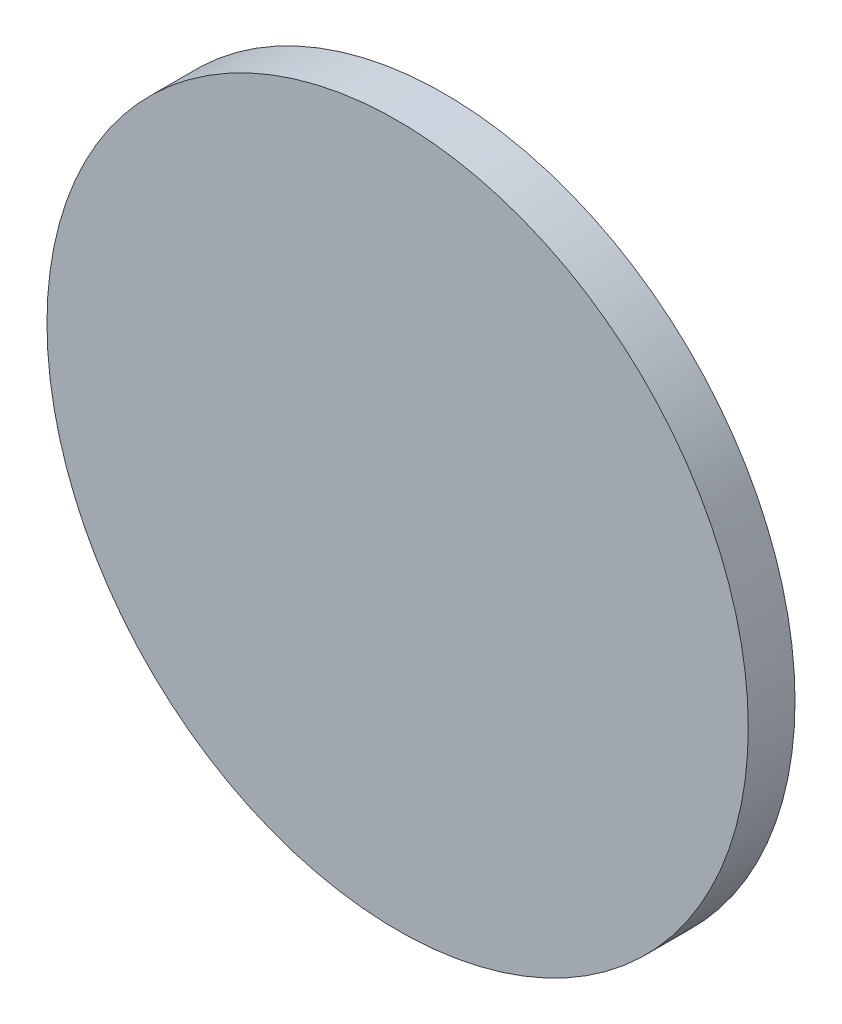
SolidWorks part; units mm, degrees
ref_plane "Front Plane" through (0, 0, 0) normal (0, 0, 1) x (1, 0, 0)
ref_plane "Top Plane" through (0, 0, 0) normal (0, 1, 0) x (1, 0, 0)
ref_plane "Right Plane" through (0, 0, 0) normal (1, 0, 0) x (0, 0, -1)
sketch "Sketch1" plane through (0, 0, 0) normal (0, 0, 1) x (1, 0, 0)
  circle A0 centre (0, 0) radius 75
  dimension "D1" = 150
extrude "Boss-Extrude1" add sketch "Sketch1" along normal blind 10
